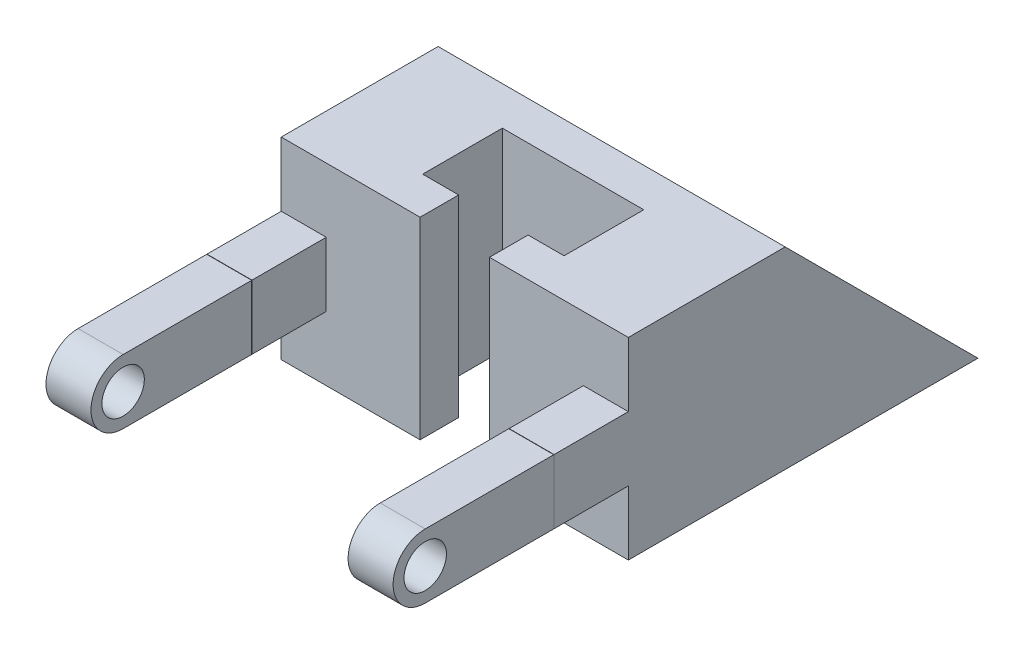
SolidWorks part; units mm, degrees
ref_plane "前视基准面" through (0, 0, 0) normal (0, 0, 1) x (1, 0, 0)
ref_plane "上视基准面" through (0, 0, 0) normal (0, 1, 0) x (1, 0, 0)
ref_plane "右视基准面" through (0, 0, 0) normal (1, 0, 0) x (0, 0, -1)
sketch "草图1" plane through (0, 0, 0) normal (0, 1, 0) x (1, 0, 0)
  line L0 (-5.5, 0) -> (5.5, 0)
  line L1 (5.5, 0) -> (5.5, -6.2)
  line L2 (5.5, -6.2) -> (2.7, -6.2)
  line L3 (2.7, -6.2) -> (2.7, -9.2)
  line L4 (2.7, -9.2) -> (5.5, -9.2)
  line L5 (5.5, -9.2) -> (5.5, -17)
  line L6 (5.5, -17) -> (8.5, -17)
  line L8 (-8.5, 3) -> (8.5, 3)
  line L9 (8.5, 3) -> (8.5, -17)
  line L10 (-5.5, -17) -> (-8.5, -17)
  line L11 (-5.5, -9.2) -> (-5.5, -17)
  line L12 (-2.7, -9.2) -> (-5.5, -9.2)
  line L13 (-2.7, -6.2) -> (-2.7, -9.2)
  line L14 (-5.5, -6.2) -> (-2.7, -6.2)
  line L15 (-5.5, 0) -> (-5.5, -6.2)
  line L16 (-8.5, 3) -> (-8.5, -17)
extrude "凸台-拉伸2" add sketch "草图1" along normal blind 15
sketch "草图2" plane through (8.5, 0, 0) normal (1, 0, 0) x (0, 0, -1)
  line L0 (-17, 15) -> (-17, 10)
  line L1 (-17, 15) -> (-17, 0) construction
  line L2 (-17, 0) -> (-17, 5)
  line L3 (-17, 15) -> (-9.2, 15)
  line L4 (-17, 15) -> (3, 15) construction
  line L5 (-9.2, 15) -> (-9.2, 10)
  line L6 (-9.2, 10) -> (-17, 10)
  line L7 (-17, 5) -> (-9.2, 5)
  line L8 (-9.2, 5) -> (-9.2, 0)
  line L9 (-17, 0) -> (3, 0) construction
  line L10 (-9.2, 0) -> (-17, 0)
extrude "切除-拉伸1" cut sketch "草图2" against normal blind 23
sketch "草图3" plane through (-8.5, 0, 0) normal (-1, 0, 0) x (0, 0, 1)
  line L0 (-3, 15) -> (-3, 7.5)
  line L1 (-3, 15) -> (-3, 0) construction
  line L2 (-3, 7.5) -> (15, 7.5)
  circle A0 centre (15, 7.5) radius 1.65
extrude "切除-拉伸2" cut sketch "草图3" against normal blind 23
sketch "草图4" plane through (0, 0, 17) normal (0, 0, 1) x (1, 0, 0)
  line L0 (-8.5, 10) -> (-5.5, 10)
  line L1 (-8.5, 10) -> (-8.5, 5.005)
  line L2 (-5.5, 10) -> (-5.5, 5.005)
  line L3 (-8.5, 5.005) -> (-5.5, 5.005)
  line L4 (-5.5, 10) -> (-5.5, 5) construction
  line L5 (-8.5, 10) -> (-5.5, 10) construction
  line L6 (5.5, 10) -> (8.5, 10)
  line L7 (5.5, 10) -> (5.5, 4.9814)
  line L8 (8.5, 10) -> (8.5, 4.9814)
  line L9 (5.5, 4.9814) -> (8.5, 4.9814)
extrude "凸台-拉伸3" add sketch "草图4" along normal blind 0.5
sketch "草图5" plane through (-8.5, 0, 0) normal (-1, 0, 0) x (0, 0, 1)
  line L0 (15, 10) -> (17.5, 10)
  line L1 (17.5, 10) -> (17.5, 7.5)
  line L2 (17.5, 7.5) -> (17.5, 5.005)
  line L3 (17.5, 5.005) -> (15, 5)
  line L4 (17.5, 5.005) -> (17.7329, 2.2884)
  line L5 (17.7329, 2.2884) -> (15, 5)
  circle A0 centre (15, 7.5) radius 2.5
extrude "切除-拉伸4" cut sketch "草图5" against normal blind 20.5
sketch "草图7" plane through (-8.5, 0, 0) normal (-1, 0, 0) x (0, 0, 1)
  line L0 (-3, 15) -> (-3, 0)
  line L1 (-3, 0) -> (-18, 0)
  line L2 (-18, 0) -> (-3, 15)
extrude "凸台-拉伸4" add sketch "草图7" against normal blind 17
sketch "草图8" plane through (0, 15, 0) normal (0, 1, 0) x (1, 0, 0)
  line L0 (-8.5, 3) -> (-8.5, 5)
  line L1 (-8.5, 3) -> (-8.5, 18) construction
  line L2 (-8.5, 5) -> (-6.5, 5)
  line L3 (-6.5, 5) -> (-6.5, 18)
  line L4 (-6.5, 5) -> (8.5, 5)
  line L5 (8.5, 3) -> (8.5, 18) construction
  line L6 (8.5, 5) -> (6.5, 5)
  line L7 (6.5, 5) -> (6.5, 18)
  line L8 (6.5, 18) -> (-6.5, 18)
extrude "切除-拉伸5" cut sketch "草图8" against normal blind 14 contours L7 L8 L3 L4
sketch "草图9" plane through (0, 1, 0) normal (0, 1, 0) x (1, 0, 0)
  line L0 (0, 5) -> (0, 8)
  line L1 (-6.5, 5) -> (6.5, 5) construction
  line L2 (0, 8) -> (-4, 8)
  circle A0 centre (-4, 8) radius 1.65
  circle A1 centre (4, 8) radius 1.65
  circle A2 centre (-4, 14) radius 1.65
  circle A3 centre (4, 14) radius 1.65
  dimension "D1" = 2
extrude "切除-拉伸6" cut sketch "草图9" against normal blind 14
sketch "草图10" plane through (-8.5, 0, 0) normal (-1, 0, 0) x (0, 0, 1)
  line L0 (15, 10) -> (25, 10)
  line L2 (15, 5) -> (25, 5)
  line L3 (25, 5) -> (25, 10)
  line L4 (15, 10) -> (15, 5)
  circle A0 centre (25, 7.5) radius 2.5
  circle A1 centre (25, 7.5) radius 1.65
  circle M1 centre (15, 7.5) radius 1.65
  arc M3 (15, 5) -> (15, 10) centre (15, 7.5) ccw
extrude "凸台-拉伸8" add sketch "草图10" along normal mid plane 50 contours A1 L3 A0 | A1 L3 A0 | A0 L0 L2 M3 | L4 M3 M1 | L4 M1 | L4 M1
sketch "草图11" plane through (0, 10, 0) normal (0, 1, 0) x (1, 0, 0)
  line L0 (-8.5, -15) -> (-16.5, -15)
  line L1 (-33.5, -15) -> (-8.5, -15) construction
  line L2 (-8.5, -15) -> (-8.5, -35.0128)
  line L3 (-8.5, -15) -> (-16.7588, -15)
  line L4 (-8.5, -35.0128) -> (-16.7588, -35.0128)
  line L5 (-16.7588, -15) -> (-16.7588, -35.0128)
  line L6 (-16.7588, -35.0128) -> (-38.7573, -35.0128)
  line L7 (-16.7588, -35.0128) -> (-16.7588, 0.8187)
  line L8 (-38.7573, -35.0128) -> (-38.7573, 0.8187)
  line L9 (-16.7588, 0.8187) -> (-38.7573, 0.8187)
  line M3 (-8.5, -15) -> (-33.5, -15)
  line M4 (-33.5, -15) -> (-33.5, -25)
  line M5 (-33.5, -25) -> (16.5, -25)
extrude "切除-拉伸8" cut sketch "草图11" against normal blind 50 contours L7 L9 L8 L6 L5 M5 M4 M3 | L5 M3 M4 M5
sketch "草图13" plane through (8.5, 0, 0) normal (1, 0, 0) x (0, 0, -1)
  line L0 (18, 0) -> (-9.2, 0)
  line L1 (-9.2, 0) -> (-9.2, 5)
  line L2 (-9.2, 5) -> (-15, 5)
  line L3 (-15, 5) -> (-15, 10)
  line L4 (-15, 10) -> (-9.2, 10)
  line L5 (-9.2, 10) -> (-9.2, 15)
  line L6 (-9.2, 15) -> (3, 15)
  line L7 (3, 15) -> (18, 0)
extrude "凸台-拉伸9" add sketch "草图13" along normal blind 8
sketch "草图14" plane through (-8.5, 0, 0) normal (-1, 0, 0) x (0, 0, 1)
  line L0 (15, 10) -> (15, 5)
  line L1 (9.2, 5) -> (15, 5) construction
  line L2 (15, 5) -> (9.2, 5)
  line L3 (9.2, 5) -> (9.2, 0)
  line L4 (9.2, 0) -> (-18, 0)
  line L5 (-18, 0) -> (-3, 15)
  line L6 (-3, 15) -> (9.2, 15)
  line L7 (9.2, 15) -> (9.2, 10)
  line L8 (9.2, 10) -> (15, 10)
extrude "凸台-拉伸11" add sketch "草图14" along normal blind 8
sketch "草图15" plane through (0, 10, 0) normal (0, 1, 0) x (1, 0, 0)
  line L0 (-5.5, -15) -> (-13.5, -15)
  line L1 (-13.5, -15) -> (-13.5, -9.2)
  line L2 (-16.5, -9.2) -> (-5.5, -9.2) construction
  line L3 (5.5, -15) -> (13.5, -15)
  line L4 (13.5, -15) -> (13.5, -9.2)
  line L5 (5.5, -9.2) -> (16.5, -9.2) construction
  line L6 (13.5, -9.2) -> (-13.5, -9.2)
  line L7 (5.5, -15) -> (-5.5, -15)
extrude "切除-拉伸9" cut sketch "草图15" against normal blind 8
sketch "草图16" plane through (0, 0, 15) normal (0, 0, -1) x (-1, 0, 0)
  line L4 (16.7588, 10) -> (16.7588, 5)
  line L5 (16.7588, 10) -> (16.5026, 10)
  line L6 (16.7588, 5) -> (16.5026, 5)
  line L7 (16.5026, 10) -> (16.5026, 5)
extrude "切除-拉伸11" cut sketch "草图16" against normal mid plane 80
sketch "草图17" plane through (0, 10, 0) normal (0, 1, 0) x (1, 0, 0)
  line L0 (13.5, -15) -> (-13.5, -15)
  line L1 (13.5, -15) -> (13.5, -41.9709)
  line L2 (-13.5, -15) -> (-13.5, -41.9709)
  line L3 (13.5, -41.9709) -> (-13.5, -41.9709)
  line L4 (-13.5, -9.2) -> (-13.5, -15) construction
sketch "草图18" plane through (-13.5, 0, 0) normal (1, 0, 0) x (0, 0, -1)
  line L0 (-9.2, 5) -> (-9.2, 10)
  line L1 (-9.2, 5) -> (-14.9767, 5)
  line L2 (-9.2, 10) -> (-14.9767, 10)
  line L3 (-14.9767, 5) -> (-14.9767, 10)
extrude "凸台-拉伸13" add sketch "草图18" along normal blind 29
sketch "草图19" plane through (0, 5, 0) normal (0, -1, 0) x (1, 0, 0)
  line L0 (0, 9.2) -> (-10, 9.2)
  line L1 (2.7, 9.2) -> (-2.7, 9.2) construction
  line L2 (-16.5, 9.2) -> (-2.7, 9.2) construction
  line L3 (0, 9.2) -> (10, 9.2)
  line L4 (2.7, 9.2) -> (16.5, 9.2) construction
  line L5 (10, 9.2) -> (10, 29.3376)
  line L7 (-10, 29.3376) -> (10, 29.3376)
  line L8 (-10, 29.3376) -> (-10, 9.2)
extrude "切除-拉伸13" cut sketch "草图19" against normal blind 24
sketch "草图20" plane through (0, 0, 0) normal (0, -1, 0) x (1, 0, 0)
  line L0 (-16.5, 9.2) -> (-13.5, 9.2)
  line L1 (-16.5, 9.2) -> (-2.7, 9.2) construction
  line L2 (16.5, 9.2) -> (13.5, 9.2)
  line L3 (2.7, 9.2) -> (16.5, 9.2) construction
  line L4 (13.5, 9.2) -> (13.5, -18)
  line L5 (16.5, -18) -> (-16.5, -18) construction
  line L6 (13.5, -18) -> (16.5, -18)
  line L7 (16.5, -18) -> (16.5, 42.2455)
  line L8 (16.5, 42.2455) -> (13.5, 42.2455)
  line L9 (13.5, 42.2455) -> (13.5, 9.2)
  line L10 (-13.5, 9.2) -> (-13.5, 43.5506)
  line L11 (-13.5, 43.5506) -> (-16.5, 43.5506)
  line L12 (-16.5, 43.5506) -> (-16.5, -18)
  line L13 (-16.5, -18) -> (-16.5, 9.2) construction
  line L14 (-16.5, -18) -> (-13.5, -18)
  line L15 (-13.5, -18) -> (-13.5, 9.2)
  line L16 (16.5, 42.2455) -> (39.5508, 38.5955)
  line L17 (39.5508, 38.5955) -> (42.4056, -22.5054)
  line L18 (42.4056, -22.5054) -> (16.5, -18)
  line L19 (-16.5, 43.5506) -> (-30.1917, 43.5506)
  line L20 (-30.1917, 43.5506) -> (-32.6273, -13.9343)
  line L21 (-32.6273, -13.9343) -> (-16.5, -18)
  line M4 (-2.7, 9.2) -> (-16.5, 9.2)
  line M5 (-16.5, 9.2) -> (-16.5, -18)
  line M6 (-16.5, -18) -> (16.5, -18)
  line M7 (16.5, -18) -> (16.5, 9.2)
  line M8 (16.5, 9.2) -> (2.7, 9.2)
extrude "切除-拉伸16" cut sketch "草图20" against normal through all contours L18 L17 L16 L7 M7 | L8 L9 L7 M8 | L4 M8 M6 M7 | L11 L12 L10 M4 | L15 M6 M4 M5 | L20 L21 L12 L19 M5
